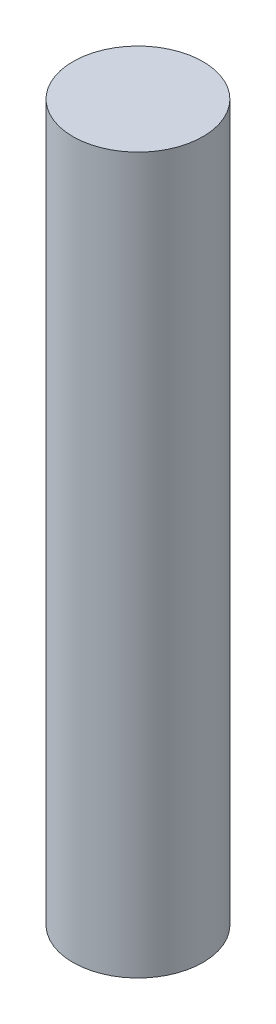
SolidWorks part; units mm, degrees
ref_plane "Front Plane" through (0, 0, 0) normal (0, 0, 1) x (1, 0, 0)
ref_plane "Top Plane" through (0, 0, 0) normal (0, 1, 0) x (1, 0, 0)
ref_plane "Right Plane" through (0, 0, 0) normal (1, 0, 0) x (0, 0, -1)
sketch "Sketch8" plane through (0, 0, 0) normal (0, 1, 0) x (1, 0, 0)
  circle A0 centre (0, 0) radius 5
  dimension "D1" = 10
extrude "Boss-Extrude2" add sketch "Sketch8" along normal blind 55
